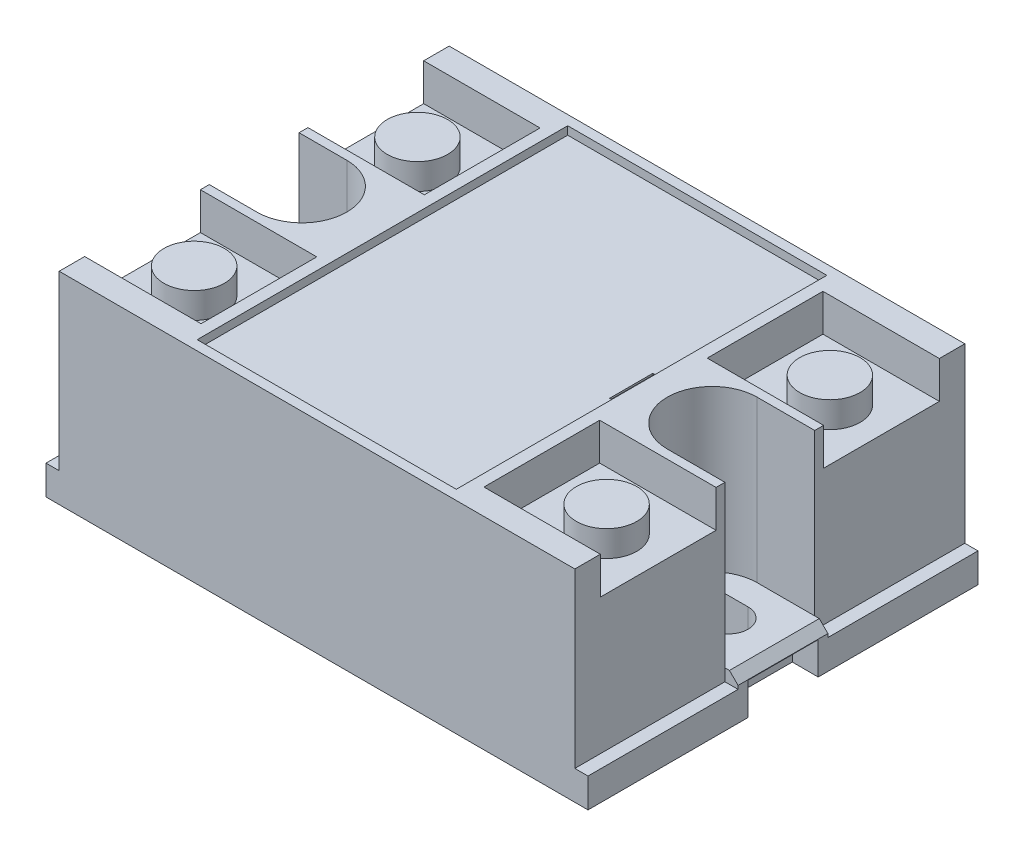
SolidWorks part; units mm, degrees
ref_plane "Front Plane" through (0, 0, 0) normal (0, 0, 1) x (1, 0, 0)
ref_plane "Top Plane" through (0, 0, 0) normal (0, 1, 0) x (1, 0, 0)
ref_plane "Right Plane" through (0, 0, 0) normal (1, 0, 0) x (0, 0, -1)
sketch "Sketch1" plane through (0, 0, 0) normal (0, 1, 0) x (1, 0, 0)
  line L1 (-31.375, -22.575) -> (31.375, -22.575)
  line L2 (-31.375, -22.575) -> (-31.375, 22.575)
  line L3 (-31.375, 22.575) -> (31.375, 22.575)
  line L4 (31.375, -22.575) -> (31.375, 22.575)
  line L5 (-31.375, -22.575) -> (31.375, 22.575) construction
  line L6 (-31.375, 22.575) -> (31.375, -22.575) construction
  point P0 (0, 0)
  dimension "D1" = 62.75
  dimension "D2" = 45.15
extrude "Boss-Extrude1" add sketch "Sketch1" along normal blind 23.4
sketch "Sketch2" plane through (0, 23.4, 0) normal (0, 1, 0) x (1, 0, 0)
  line L1 (-15, -21.45) -> (15, -21.45)
  line L2 (-15, -21.45) -> (-15, 21.45)
  line L3 (-15, 21.45) -> (15, 21.45)
  line L4 (15, -21.45) -> (15, 21.45)
  line L5 (-15, -21.45) -> (15, 21.45) construction
  line L6 (-15, 21.45) -> (15, -21.45) construction
  point P0 (0, 0)
  dimension "D1" = 30
  dimension "D2" = 42.9
extrude "Cut-Extrude1" cut sketch "Sketch2" against normal blind 0.95
sketch "Sketch3" plane through (0, 23.4, 0) normal (0, 1, 0) x (1, 0, 0)
  line L0 (-31.375, 22.575) -> (-31.375, -22.575) construction
  line L1 (-31.375, 19.625) -> (-16.375, 19.625)
  line L2 (-31.375, 19.625) -> (-31.375, 6.225)
  line L3 (-31.375, 6.225) -> (-16.375, 6.225)
  line L4 (-16.375, 19.625) -> (-16.375, 6.225)
  line L5 (-31.375, 0) -> (31.375, 0) construction
  line L6 (31.375, -22.575) -> (31.375, 22.575) construction
  line L7 (0, 22.575) -> (0, -22.575) construction
  line L8 (31.375, 22.575) -> (-31.375, 22.575) construction
  line L9 (-31.375, -22.575) -> (31.375, -22.575) construction
  line L10 (-16.375, -19.625) -> (-16.375, -6.225)
  line L11 (-31.375, -6.225) -> (-16.375, -6.225)
  line L12 (-31.375, -19.625) -> (-31.375, -6.225)
  line L13 (-31.375, -19.625) -> (-16.375, -19.625)
  line L14 (31.375, -19.625) -> (16.375, -19.625)
  line L15 (31.375, -19.625) -> (31.375, -6.225)
  line L16 (31.375, -6.225) -> (16.375, -6.225)
  line L17 (16.375, -19.625) -> (16.375, -6.225)
  line L18 (16.375, 19.625) -> (16.375, 6.225)
  line L19 (31.375, 6.225) -> (16.375, 6.225)
  line L20 (31.375, 19.625) -> (31.375, 6.225)
  line L21 (31.375, 19.625) -> (16.375, 19.625)
  dimension "D1" = 13.4
  dimension "D2" = 2.95
  dimension "D3" = 15
extrude "Cut-Extrude2" cut sketch "Sketch3" against normal blind 4.3
sketch "Sketch4" plane through (0, 19.1, 0) normal (0, 1, 0) x (1, 0, 0)
  line L0 (-23.875, 19.625) -> (-23.875, 6.225) construction
  line L1 (-16.375, 19.625) -> (-31.375, 19.625) construction
  line L2 (-31.375, 6.225) -> (-16.375, 6.225) construction
  line L3 (0, 22.575) -> (0, -22.575) construction
  line L4 (31.375, 22.575) -> (-31.375, 22.575) construction
  line L5 (-31.375, -22.575) -> (31.375, -22.575) construction
  line L6 (-31.375, 0) -> (31.375, 0) construction
  line L7 (-31.375, 6.225) -> (-31.375, -6.225) construction
  line L8 (31.375, -6.225) -> (31.375, 6.225) construction
  line L9 (-23.875, -19.625) -> (-23.875, -6.225) construction
  line L10 (23.875, -19.625) -> (23.875, -6.225) construction
  line L11 (23.875, 19.625) -> (23.875, 6.225) construction
  circle A0 centre (-23.875, 12.925) radius 3.5
  circle A1 centre (-23.875, -12.925) radius 3.5
  circle A2 centre (23.875, -12.925) radius 3.5
  circle A3 centre (23.875, 12.925) radius 3.5
  dimension "D1" = 7
extrude "Boss-Extrude2" add sketch "Sketch4" along normal blind 3
sketch "Sketch5" plane through (0, 23.4, 0) normal (0, 1, 0) x (1, 0, 0)
  line L0 (-31.375, 0) -> (-24.325, 0) construction
  line L3 (31.375, 0) -> (23.175, 0) construction
  line L4 (31.375, -6.225) -> (31.375, 6.225) construction
  line L5 (31.375, -5.2) -> (23.175, -5.2)
  line L6 (31.375, 5.2) -> (23.175, 5.2)
  line L7 (-31.375, 6.225) -> (-31.375, -6.225) construction
  line L8 (-31.375, 5.2) -> (-24.325, 5.2)
  line L9 (-31.375, -5.2) -> (-24.325, -5.2)
  arc A0 (31.375, -5.2) -> (31.375, 5.2) centre (31.375, 0) ccw
  arc A1 (23.175, 5.2) -> (23.175, -5.2) centre (23.175, 0) ccw
  arc A2 (-31.375, 5.2) -> (-31.375, -5.2) centre (-31.375, 0) ccw
  arc A3 (-24.325, -5.2) -> (-24.325, 5.2) centre (-24.325, 0) ccw
  point P4 (-27.85, 0)
  point P11 (27.275, 0)
  dimension "D1" = 10.4
  dimension "D2" = 13.4
  dimension "D3" = 12.25
extrude "Cut-Extrude3" cut sketch "Sketch5" against normal blind 18.6
sketch "Sketch6" plane through (0, 22.45, 0) normal (0, 1, 0) x (1, 0, 0)
  line L0 (31.375, 0) -> (0, 0) construction
  line L1 (31.375, -5.2) -> (31.375, 5.2) construction
  line L2 (14, 2.5) -> (14, -2.5)
  line L3 (15, -21.45) -> (15, 21.45) construction
  dimension "D1" = 1
  dimension "D2" = 5
extrude "Cut-Extrude-Thin1" cut sketch "Sketch6" against normal blind 1 and the other way through all thin
sketch "Sketch7" plane through (0, 4.8, 0) normal (0, 1, 0) x (1, 0, 0)
  line L0 (22.275, 0) -> (25.075, 0) construction
  line L1 (22.275, 2.25) -> (25.075, 2.25)
  line L2 (22.275, -2.25) -> (25.075, -2.25)
  line L3 (31.375, -5.2) -> (31.375, 5.2) construction
  arc A0 (22.275, 2.25) -> (22.275, -2.25) centre (22.275, 0) ccw
  arc A1 (25.075, -2.25) -> (25.075, 2.25) centre (25.075, 0) ccw
  point P3 (23.675, 0)
  dimension "D3" = 7.3
  dimension "D1" = 4.05
  dimension "D2" = 4.5
extrude "Cut-Extrude4" cut sketch "Sketch7" against normal through all
sketch "Sketch8" plane through (0, 4.8, 0) normal (0, 1, 0) x (1, 0, 0)
  line L0 (22.275, 0) -> (-31.375, 0) construction
  line L1 (-31.375, 5.2) -> (-31.375, -5.2) construction
  circle A0 centre (-23.825, 0) radius 2.25
  arc A3 (-24.325, -5.2) -> (-24.325, 5.2) centre (-24.325, 0) ccw construction
  dimension "D1" = 4.5
  dimension "D2" = 5.7
extrude "Cut-Extrude5" cut sketch "Sketch8" against normal through all
sketch "Sketch9" plane through (0, 23.4, 0) normal (0, 1, 0) x (1, 0, 0)
  line L0 (-31.375, -22.575) -> (31.375, -22.575) construction
  line L1 (-31.375, 22.575) -> (-29.85, 22.575)
  line L2 (-31.375, 22.575) -> (-31.375, -22.575)
  line L3 (-31.375, -22.575) -> (-29.85, -22.575)
  line L4 (-29.85, 22.575) -> (-29.85, -22.575)
  line L5 (0, 22.575) -> (0, -22.575) construction
  line L6 (31.375, 22.575) -> (-31.375, 22.575) construction
  line L7 (29.85, 22.575) -> (29.85, -22.575)
  line L8 (31.375, -22.575) -> (29.85, -22.575)
  line L9 (31.375, 22.575) -> (31.375, -22.575)
  line L10 (31.375, 22.575) -> (29.85, 22.575)
  dimension "D1" = 59.7
extrude "Cut-Extrude6" cut sketch "Sketch9" against normal blind 20
sketch "Sketch11" plane through (0, 3.4, 0) normal (0, 1, 0) x (1, 0, 0)
  line L0 (-31.375, 22.575) -> (-31.375, -22.575) construction
  line L1 (-29.85, 5.2) -> (-31.375, 5.2)
  line L2 (-29.85, 5.2) -> (-29.85, -5.2)
  line L3 (-29.85, -5.2) -> (-31.375, -5.2)
  line L4 (-31.375, 5.2) -> (-31.375, -5.2)
  line L5 (31.375, -22.575) -> (31.375, 22.575) construction
  line L6 (29.85, 5.2) -> (31.375, 5.2)
  line L7 (29.85, 5.2) -> (29.85, -5.2)
  line L8 (29.85, -5.2) -> (31.375, -5.2)
  line L9 (31.375, 5.2) -> (31.375, -5.2)
  line L10 (29.85, 22.575) -> (29.85, -22.575) construction
extrude "Boss-Extrude3" add sketch "Sketch11" along normal up to surface (1.4 mm away) up to face at (-25.7875, 4.8, 0)
chamfer "Chamfer1" distance 1 angle 45 2 edges at (31.375, 4.8, 0) (-31.375, 4.8, 0)
sketch "Sketch10" plane through (0, 0, 0) normal (0, -1, 0) x (1, 0, 0)
  line L0 (0, 22.575) -> (0, -22.575) construction
  line L1 (-31.375, 22.575) -> (31.375, 22.575) construction
  line L2 (31.375, -22.575) -> (-31.375, -22.575) construction
  line L3 (-31.375, 0) -> (31.375, 0) construction
  line L4 (-31.375, -22.575) -> (-31.375, 22.575) construction
  line L5 (31.375, 22.575) -> (31.375, -22.575) construction
  line L6 (-28.375, 4.075) -> (-31.375, -4.075) construction
  line L7 (28.375, -4.075) -> (31.375, -4.075)
  line L8 (28.375, -4.075) -> (28.375, 4.075)
  line L9 (28.375, 4.075) -> (31.375, 4.075)
  line L10 (31.375, -4.075) -> (31.375, 4.075)
  line L11 (28.375, -4.075) -> (31.375, 4.075) construction
  line L12 (28.375, 4.075) -> (31.375, -4.075) construction
  line L13 (-28.375, -4.075) -> (-31.375, 4.075) construction
  line L14 (-31.375, -4.075) -> (-31.375, 4.075)
  line L15 (-28.375, 4.075) -> (-31.375, 4.075)
  line L16 (-28.375, -4.075) -> (-28.375, 4.075)
  line L17 (-28.375, -4.075) -> (-31.375, -4.075)
  point P12 (29.875, 0)
  point P21 (-29.875, 0)
  dimension "D1" = 8.15
  dimension "D2" = 3
extrude "Cut-Extrude7" cut sketch "Sketch10" against normal blind 3.75
sketch "Sketch13"
sketch "Esboço1" plane through (0, 0, 0) normal (0, -1, 0) x (1, 0, 0)
  circle A0 centre (-23.825, 0) radius 2.25
  circle A1 centre (22.463, 0) radius 2.25
  point P6 (25.075, 0)
  point P7 (0, 0)
  point P8 (22.463, 0)
  dimension "D1" = 4.5
